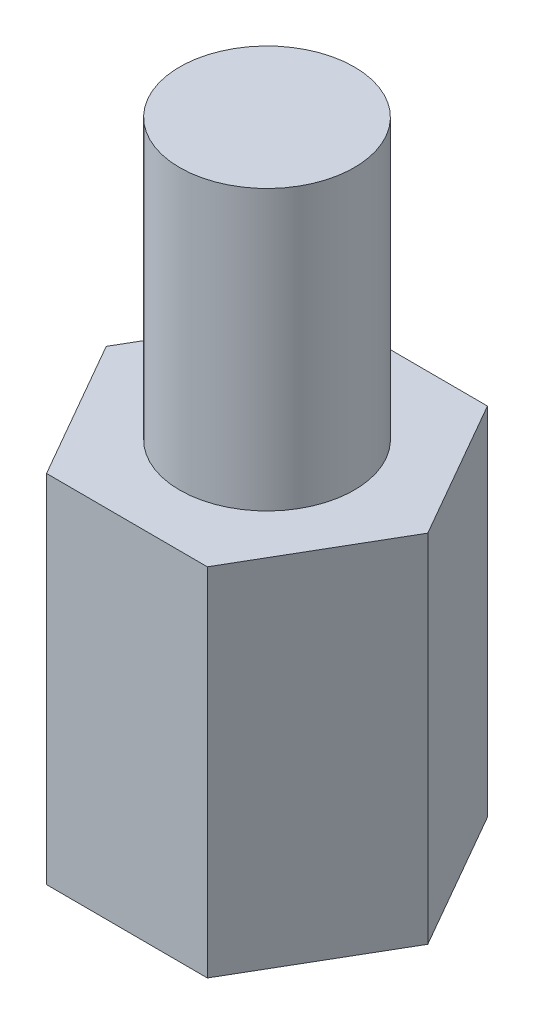
SolidWorks part; units mm, degrees
ref_plane "Front Plane" through (0, 0, 0) normal (0, 0, 1) x (1, 0, 0)
ref_plane "Top Plane" through (0, 0, 0) normal (0, 1, 0) x (1, 0, 0)
ref_plane "Right Plane" through (0, 0, 0) normal (1, 0, 0) x (0, 0, -1)
sketch "Sketch1" plane through (0, 0, 0) normal (0, 1, 0) x (1, 0, 0)
  line L1 (1.1606, 1.9966) -> (-1.1487, 2.0034)
  line L2 (-1.1487, 2.0034) -> (-2.3094, 0.0069)
  line L3 (-2.3094, 0.0069) -> (-1.1606, -1.9966)
  line L4 (-1.1606, -1.9966) -> (1.1487, -2.0034)
  line L5 (1.1487, -2.0034) -> (2.3094, -0.0069)
  line L6 (2.3094, -0.0069) -> (1.1606, 1.9966)
  circle A1 centre (0, 0) radius 2 construction
  dimension "D1" = 4
extrude "Boss-Extrude1" add sketch "Sketch1" along normal blind 5.1
sketch "Sketch2" plane through (0, 5.1, 0) normal (0, 1, 0) x (1, 0, 0)
  circle A0 centre (0, 0) radius 1.25
  dimension "D1" = 2.5
extrude "Boss-Extrude2" add sketch "Sketch2" along normal blind 4
sketch "Sketch3" plane through (0, 0, 0) normal (0, -1, 0) x (1, 0, 0)
  circle A0 centre (0, 0) radius 1.27
  dimension "D1" = 2.54
extrude "Cut-Extrude1" cut sketch "Sketch3" against normal blind 2
